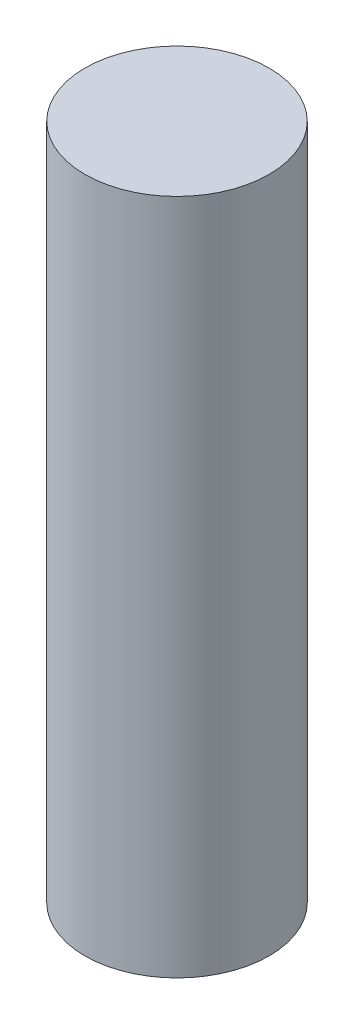
SolidWorks part; units mm, degrees
ref_plane "Front Plane" through (0, 0, 0) normal (0, 0, 1) x (1, 0, 0)
ref_plane "Top Plane" through (0, 0, 0) normal (0, 1, 0) x (1, 0, 0)
ref_plane "Right Plane" through (0, 0, 0) normal (1, 0, 0) x (0, 0, -1)
sketch "Sketch1" plane through (0, 0, 0) normal (0, 1, 0) x (1, 0, 0)
  circle A0 centre (0, 0) radius 2.45
  dimension "D1" = 4.9
extrude "Boss-Extrude1" add sketch "Sketch1" along normal blind 18
